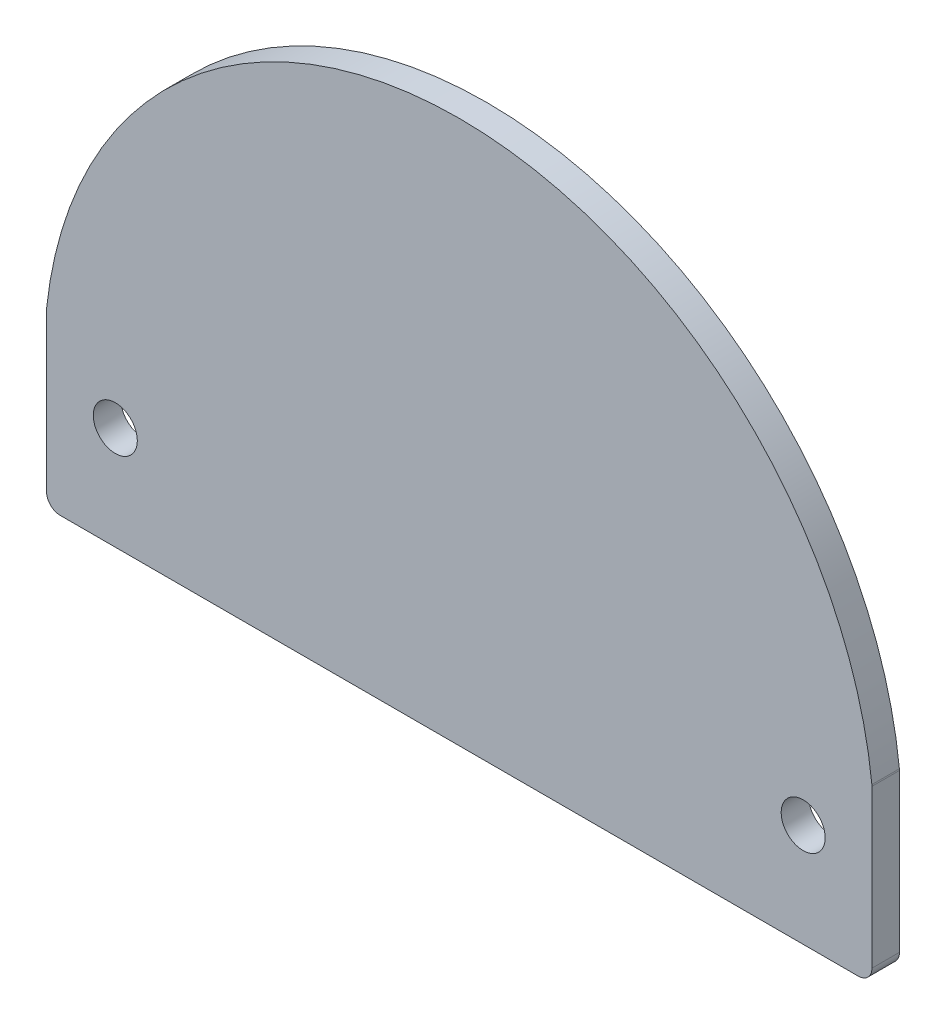
SolidWorks part; units mm, degrees
ref_plane "Спереди" through (0, 0, 0) normal (0, 0, 1) x (1, 0, 0)
ref_plane "Сверху" through (0, 0, 0) normal (0, 1, 0) x (1, 0, 0)
ref_plane "Справа" through (0, 0, 0) normal (1, 0, 0) x (0, 0, -1)
sketch "Эскиз1" plane through (0, 0, 0) normal (0, 0, 1) x (1, 0, 0)
  line L1 (-30, 0) -> (30, 0) construction
  line L2 (-30, 0) -> (-30, -12.5)
  line L3 (-30, -12.5) -> (30, -12.5)
  line L4 (30, 0) -> (30, -12.5)
  arc A0 (-30, 0) -> (30, 0) centre (0, -3.1667) cw
  point P4 (0, 0)
  point P7 (0, 27)
  dimension "D1" = 60
  dimension "D2" = 12.5
  dimension "D3" = 27
extrude "тело" add sketch "Эскиз1" along normal blind 2
sketch "Эскиз2" plane through (0, 0, 2) normal (0, 0, 1) x (1, 0, 0)
  line L0 (0, 0) -> (0, -12.5) construction
  line L1 (-30, 0) -> (30, 0) construction
  line L2 (-30, -12.5) -> (30, -12.5) construction
  line L3 (-25, -5) -> (25, -5) construction
  line L4 (-30, -12.5) -> (30, -12.5) construction
  circle A0 centre (-25, -5) radius 1.6
  circle A1 centre (25, -5) radius 1.6
  point P9 (0, -5)
  dimension "D1" = 3.2
  dimension "D2" = 50
  dimension "D3" = 7.5
extrude "крепежные отверстия" cut sketch "Эскиз2" against normal through all and the other way through all
fillet "Скругление1" radius 1 4 edges at (-30, -12.5, 1) (30, -12.5, 1) (30, 0, 1) (-30, 0, 1)
